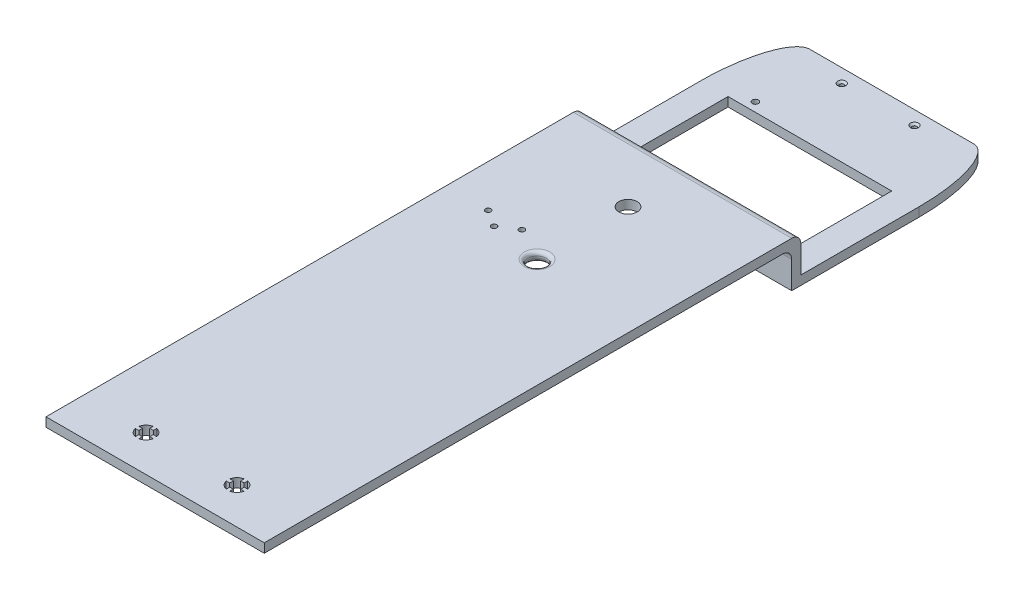
SolidWorks part; units mm, degrees
ref_plane "Front Plane" through (0, 0, 0) normal (0, 0, 1) x (1, 0, 0)
ref_plane "Top Plane" through (0, 0, 0) normal (0, 1, 0) x (1, 0, 0)
ref_plane "Right Plane" through (0, 0, 0) normal (1, 0, 0) x (0, 0, -1)
sketch "Sketch1" plane through (0, 0, 0) normal (1, 0, 0) x (0, 0, -1)
  line L1 (0, 0) -> (-5, 0)
  line L2 (0, 0) -> (0, 25)
  line L3 (0, 25) -> (-5, 25)
  line L4 (-5, 0) -> (-5, 25)
  line L5 (0, 0) -> (110, 0)
  line L6 (0, 0) -> (0, 5)
  line L7 (0, 5) -> (110, 5)
  line L8 (110, 0) -> (110, 5)
  line L9 (-5, 25) -> (-295, 25)
  line L10 (-5, 25) -> (-5, 20)
  line L11 (-5, 20) -> (-295, 20)
  line L12 (-295, 25) -> (-295, 20)
  dimension "D1" = 5
  dimension "D2" = 5
  dimension "D3" = 5
  dimension "D4" = 405
  dimension "D5" = 290
  dimension "D6" = 25
extrude "Boss-Extrude1" add sketch "Sketch1" along normal blind 120 contours L4 L1 L2 L3 | L5 L8 L7 L2 | L10 L11 L12 L9
sketch "Sketch2" plane through (0, 25, 0) normal (0, 1, 0) x (1, 0, 0)
  line L0 (120, 0) -> (120, -295) construction
  line L1 (15, 65) -> (105, 65)
  line L2 (15, 65) -> (15, 0)
  line L3 (15, 0) -> (105, 0)
  line L4 (105, 65) -> (105, 0)
  line L5 (120, 110) -> (0, 110) construction
  line L6 (120, 0) -> (120, 110) construction
  line L7 (0, 0) -> (0, 110) construction
  line L9 (120, -295) -> (0, -295) construction
  line L10 (0, 65) -> (-14.6672, 131.6222)
  line L11 (-14.6672, 131.6222) -> (15, 110)
  line L12 (105, 110) -> (141.9166, 126.0071)
  line L13 (141.9166, 126.0071) -> (120, 65)
  line L14 (84, -269) -> (86, -269)
  line L15 (34, -269) -> (36, -269)
  line L16 (34, -269) -> (34, -272)
  line L17 (34, -272) -> (36, -272)
  line L18 (36, -269) -> (36, -272)
  line L19 (34, -281) -> (36, -281)
  line L20 (34, -281) -> (34, -278)
  line L21 (34, -278) -> (36, -278)
  line L22 (36, -281) -> (36, -278)
  line L23 (41, -274) -> (38, -274)
  line L24 (41, -274) -> (41, -276)
  line L25 (41, -276) -> (38, -276)
  line L26 (38, -274) -> (38, -276)
  line L27 (29, -274) -> (32, -274)
  line L28 (29, -274) -> (29, -276)
  line L29 (29, -276) -> (32, -276)
  line L30 (32, -274) -> (32, -276)
  line L31 (84, -269) -> (84, -272)
  line L32 (84, -272) -> (86, -272)
  line L33 (86, -269) -> (86, -272)
  line L34 (84, -281) -> (86, -281)
  line L35 (84, -281) -> (84, -278)
  line L36 (84, -278) -> (86, -278)
  line L37 (86, -281) -> (86, -278)
  line L38 (91, -274) -> (88, -274)
  line L39 (91, -274) -> (91, -276)
  line L40 (91, -276) -> (88, -276)
  line L41 (88, -274) -> (88, -276)
  line L42 (79, -274) -> (82, -274)
  line L43 (79, -274) -> (79, -276)
  line L44 (79, -276) -> (82, -276)
  line L45 (82, -274) -> (82, -276)
  circle A0 centre (60, -35) radius 5
  circle A1 centre (60, -85) radius 5
  circle A2 centre (35, -275) radius 5
  circle A11 centre (85, -275) radius 5
  ellipse E0 centre (15, 65) end of major axis (15, 110) minor radius 15 (15, 110) -> (0, 65) ccw
  ellipse E1 centre (105, 65) end of major axis (105, 110) minor radius 15 (120, 65) -> (105, 110) ccw
  dimension "D1" = 10
  dimension "D9" = 10
  dimension "D2" = 60
  dimension "D3" = 35
  dimension "D4" = 50
  dimension "D5" = 45
  dimension "D6" = 15
  dimension "D7" = 15
  dimension "D8" = 110
  dimension "D10" = 25
  dimension "D11" = 50
  dimension "D12" = 20
  dimension "D13" = 2
  dimension "D14" = 6
  dimension "D15" = 6
  dimension "D16" = 1
  dimension "D17" = 1
  dimension "D18" = 3
  dimension "D19" = 3
  dimension "D20" = 3
  dimension "D21" = 2
  dimension "D22" = 6
  dimension "D23" = 6
  dimension "D24" = 1
  dimension "D25" = 1
  dimension "D26" = 3
  dimension "D27" = 3
  dimension "D28" = 3
  dimension "D29" = 15
  dimension "D30" = 15
  dimension "D31" = 45
  dimension "D32" = 45
extrude "Cut-Extrude1" cut sketch "Sketch2" against normal through all contours L22 A2 L25 L26 L23 L18 L17 L16 L27 L30 L29 L20 L21 | L37 A11 L40 L41 L38 L33 L32 L31 L42 L45 L44 L35 L36 | L2 L1 L4 L3 | L11 E0 L10 | E1 L12 L13 | A0 | A1
sketch "Sketch3" plane through (0, 5, 0) normal (0, 1, 0) x (1, 0, 0)
  line L0 (105, 110) -> (15, 110) construction
  point P0 (40, 102.5)
  point P1 (80, 102.5)
  dimension "D1" = 40
  dimension "D2" = 25
  dimension "D3" = 7.5
  dimension "D4" = 25
hole_wizard "CSK for M2 Flat Head Machine Screw1" positions "Sketch3" profile "Sketch4" countersink size "M2" standard "ANSI Metric" end condition up to next
sketch "Sketch4" plane through (40, 5, -102.5) normal (1, 0, 0) x (0, 0, 1)
  line L0 (0, 0) -> (0, 5)
  line L1 (0, 5) -> (1.2, 5)
  line L2 (1.2, 5) -> (1.2, 1)
  line L3 (1.2, 1) -> (2.2, 0)
  line L5 (2.2, 0) -> (0, 0)
  line L6 (-1.2, 1) -> (-2.2, 0) construction
  line L11 (0, -6.35) -> (0, 107.95) construction
  dimension "Thru Hole Dia." = 2.4
  dimension "Thru Hole Depth" = 5
  dimension "Near C'Sink Dia." = 4.4
  dimension "Near C'Sink Angle" = 90
sketch "Sketch5" plane through (0, 25, 0) normal (0, 1, 0) x (1, 0, 0)
  line L0 (0, 0) -> (0, -295) construction
  line L2 (120, 0) -> (0, 0) construction
  point P0 (23.25, -75.11)
  point P1 (32.5, -81.11)
  point P2 (41.75, -75.11)
  dimension "D1" = 23.25
  dimension "D2" = 18.5
  dimension "D3" = 9.25
  dimension "D4" = 6
  dimension "D5" = 75.11
hole_wizard "Ø3.0mm Dowel Hole1" positions "Sketch5" profile "Sketch6" hole size "Ø3.0" standard "ANSI Metric" end condition up to next
sketch "Sketch6" plane through (23.25, 25, 75.11) normal (1, 0, 0) x (0, 0, 1)
  line L0 (0, 0) -> (0, 5)
  line L1 (0, 5) -> (1.5, 5)
  line L2 (1.5, 5) -> (1.5, 0)
  line L5 (1.5, 0) -> (0, 0)
  line L11 (0, -6.35) -> (0, 107.95) construction
  dimension "Thru Hole Dia." = 3
  dimension "Thru Hole Depth" = 5
sketch "Sketch9" plane through (0, 0, 0) normal (-1, 0, 0) x (0, 0, 1)
  line L0 (5, 0) -> (25, 20)
  line L1 (5, 20) -> (295, 20) construction
  line L10 (-65, 5) -> (-65, 0)
  line L11 (-65, 0) -> (5, 0)
  line L12 (5, 0) -> (5, 20)
  line L13 (5, 20) -> (295, 20)
  line L14 (295, 20) -> (295, 25)
  line L15 (295, 25) -> (0, 25)
  line L16 (0, 25) -> (0, 5)
  line L17 (0, 5) -> (-65, 5)
  line L20 (5, 0) -> (5, 20)
  line L21 (5, 20) -> (25, 20)
  dimension "D1" = 45
  dimension "D2" = 0
extrude "Boss-Extrude2" add sketch "Sketch9" against normal up to surface (120 mm away) up to face at (120, 12.5, 58.75)
sketch "Sketch10" plane through (0, 0, 295) normal (0, 0, 1) x (1, 0, 0)
  line L0 (120, 20) -> (0, 20) construction
  line L1 (36.6667, 20) -> (41.6667, 20)
  line L2 (36.6667, 20) -> (36.6667, 0)
  line L3 (36.6667, 0) -> (41.6667, 0)
  line L4 (41.6667, 20) -> (41.6667, 0)
  line L5 (120, 0) -> (0, 0) construction
  line L6 (120, 20) -> (0, 20) construction
  line L7 (78.3333, 20) -> (83.3333, 20)
  line L8 (78.3333, 20) -> (78.3333, 0)
  line L9 (78.3333, 0) -> (83.3333, 0)
  line L10 (83.3333, 20) -> (83.3333, 0)
  line L12 (0, 20) -> (36.6667, 20)
  line L13 (0, 20) -> (0, 0)
  line L14 (0, 0) -> (36.6667, 0)
  line L15 (36.6667, 20) -> (36.6667, 0)
  line L16 (41.6667, 20) -> (78.3333, 20)
  line L17 (41.6667, 20) -> (41.6667, 0)
  line L18 (41.6667, 0) -> (78.3333, 0)
  line L19 (78.3333, 20) -> (78.3333, 0)
  line L20 (83.3333, 20) -> (120, 20)
  line L21 (83.3333, 20) -> (83.3333, 0)
  line L22 (83.3333, 0) -> (120, 0)
  line L23 (120, 20) -> (120, 0)
  line M6 (0, 20) -> (120, 20)
  dimension "D1" = 5
  dimension "D2" = 5
  dimension "D3" = 36.6667
  dimension "D4" = 36.6667
extrude "Cut-Extrude2" cut sketch "Sketch10" against normal blind 290 contours L13 L14 L2 M6 | L4 L18 L8 M6 | L23 L10 L22 M6
fillet "Fillet1" radius 5 4 edges at (101.6667, 20, 5) (60, 20, 5) (18.3333, 20, 5) (60, 25, 0)
sketch "Sketch11" plane through (0, 0, 0) normal (0, -1, 0) x (1, 0, 0)
  line L0 (15, -65) -> (105, -65) construction
  point P0 (25, -70)
  dimension "D1" = 10
  dimension "D2" = 5
hole_wizard "CSK for M3 Flat Head Machine Screw1" positions "Sketch11" profile "Sketch12" countersink size "M3" standard "ANSI Metric"
sketch "Sketch12" plane through (25, 0, -70) normal (1, 0, 0) x (0, 0, -1)
  line L0 (0, 0) -> (0, 6.0215)
  line L1 (0, 6.0215) -> (1.7, 5)
  line L2 (1.7, 5) -> (1.7, 1.45)
  line L3 (1.7, 1.45) -> (3.15, 0)
  line L5 (3.15, 0) -> (0, 0)
  line L6 (-1.7, 1.45) -> (-3.15, 0) construction
  line L10 (0, 6.0215) -> (-1.7, 5) construction
  line L11 (0, -6.35) -> (0, 107.95) construction
  dimension "Hole Dia." = 3.4
  dimension "Hole Depth" = 5
  dimension "Near C'Sink Dia." = 6.3
  dimension "Near C'Sink Angle" = 90
  dimension "Drill Angle" = 118
fillet "Fillet2" radius 2 2 edges at (60, 20, 80) (60, 25, 90)
